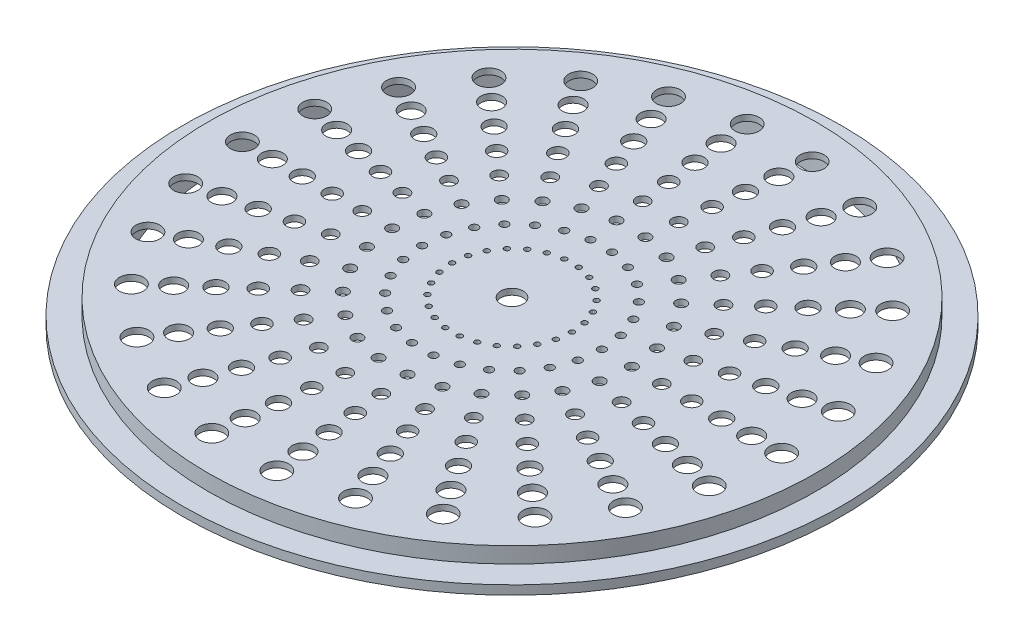
SolidWorks part; units mm, degrees
ref_plane "Front Plane" through (0, 0, 0) normal (0, 0, 1) x (1, 0, 0)
ref_plane "Top Plane" through (0, 0, 0) normal (0, 1, 0) x (1, 0, 0)
ref_plane "Right Plane" through (0, 0, 0) normal (1, 0, 0) x (0, 0, -1)
sketch "Sketch1" plane through (0, 0, 0) normal (0, 0, 1) x (1, 0, 0)
  line L0 (0, 0) -> (0, 184.7442) construction
  line L1 (-121.285, 0) -> (-128.905, 0)
  line L2 (-139.7, 1.524) -> (-139.7, 5.334)
  line L3 (-139.7, 5.334) -> (-128.905, 5.334)
  line L4 (-128.905, 5.334) -> (-128.905, 12.065)
  line L5 (-128.905, 12.065) -> (0, 12.065)
  line L6 (0, 12.065) -> (0, 9.525)
  line L7 (0, 9.525) -> (-121.285, 9.525)
  line L8 (-121.285, 9.525) -> (-121.285, 0)
  line L9 (0, 0) -> (-121.285, 0) construction
  line L10 (-139.7, 1.524) -> (-128.905, 1.524)
  line L11 (-128.905, 1.524) -> (-128.905, 0)
  dimension "D1" = 279.4
  dimension "D2" = 242.57
  dimension "D3" = 19.05
  dimension "D4" = 2.54
  dimension "D5" = 7.62
  dimension "D6" = 10.795
  dimension "D7" = 1.524
  dimension "D8" = 3.81
revolve "Revolve1" add sketch "Sketch1" angle 360 about L0
sketch "Sketch2" plane through (0, 12.065, 0) normal (0, 1, 0) x (1, 0, 0)
  line L0 (-114.3, 5.08) -> (0, 0) construction
  line L1 (0, 0) -> (-114.3, -5.08) construction
  circle A0 centre (-114.3, 0) radius 5.08
  circle A1 centre (-101.6, 0) radius 4.5111
  circle A2 centre (-88.9, 0) radius 3.9472
  circle A3 centre (-76.2, 0) radius 3.3833
  circle A4 centre (-63.5, 0) radius 2.8194
  circle A5 centre (-50.8, 0) radius 2.2556
  circle A6 centre (-38.1, 0) radius 1.6917
  circle A7 centre (-25.4, 0) radius 1.1278
  dimension "D1" = 10.16
  dimension "D3" = 12.7
  dimension "D2" = 114.3
  dimension "D4" = 12.7
  dimension "D5" = 12.7
  dimension "D6" = 12.7
  dimension "D7" = 12.7
  dimension "D8" = 12.7
  dimension "D9" = 12.7
extrude "Cut-Extrude1" cut sketch "Sketch2" against normal through all
pattern_circular "CirPattern1" count 26 over 360 about axis through (0, 0, 0) along (0, 1, 0) of "Cut-Extrude1"
sketch "Sketch3" plane through (0, 12.065, 0) normal (0, 1, 0) x (1, 0, 0)
  circle A0 centre (0, 0) radius 4.7625
  dimension "D1" = 9.525
extrude "Cut-Extrude2" cut sketch "Sketch3" against normal through all
sketch "Sketch4" plane through (0, 0, 0) normal (0, 0, 1) x (1, 0, 0)
  line L0 (-128.905, 11.684) -> (-128.905, 5.334)
  line L3 (-128.905, 12.065) -> (-128.905, 5.334) construction
  line L4 (0, 0) -> (0, 97.159) construction
  arc A0 (-128.905, 11.684) -> (-128.905, 5.334) centre (-132.8706, 8.509) cw
  dimension "D2" = 5.08
  dimension "D1" = 6.35
